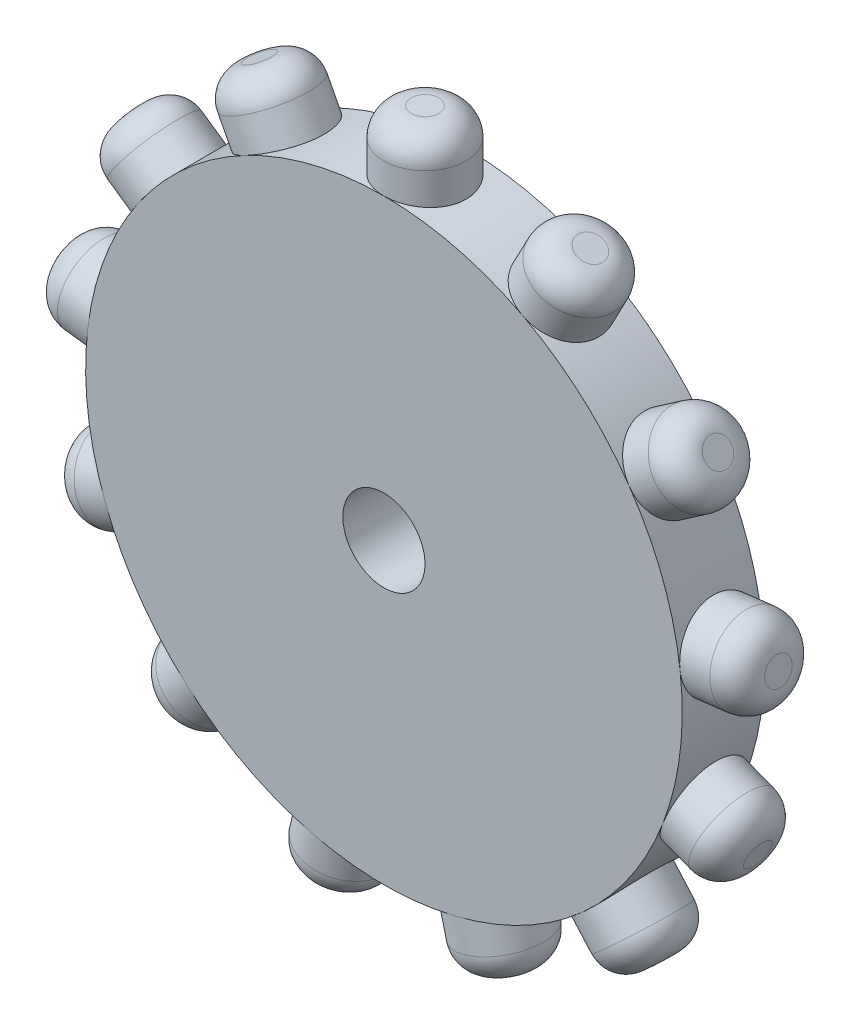
SolidWorks part; units mm, degrees
ref_plane "Front Plane" through (0, 0, 0) normal (0, 0, 1) x (1, 0, 0)
ref_plane "Top Plane" through (0, 0, 0) normal (0, 1, 0) x (1, 0, 0)
ref_plane "Right Plane" through (0, 0, 0) normal (1, 0, 0) x (0, 0, -1)
sketch "Sketch1" plane through (0, 0, 0) normal (0, 0, 1) x (1, 0, 0)
  circle A0 centre (0, 0) radius 27.6693
  dimension "D1" = 55.3385
extrude "Boss-Extrude1" add sketch "Sketch1" along normal blind 7.62
sketch "Sketch3" plane through (0, 0, 0) normal (0, 0, -1) x (-1, 0, 0)
  circle A0 centre (0, 0) radius 3.81
  dimension "D1" = 7.62
extrude "Cut-Extrude2" cut sketch "Sketch3" against normal up to next
ref_plane "Plane1" through (0, 33.02, 0) normal (0, 1, 0) x (1, 0, 0)
sketch "Sketch4" plane through (0, 33.02, 0) normal (0, 1, 0) x (1, 0, 0)
  line L0 (27.6693, 0) -> (-27.6693, 0) construction
  line L1 (-27.6693, -7.62) -> (27.6693, -7.62) construction
  line L2 (0, -55) -> (0, 55) construction
  circle A0 centre (0, -3.81) radius 3.81
extrude "Boss-Extrude3" add sketch "Sketch4" against normal up to next contours A0
fillet "Fillet3" radius 2.54 1 edges at (0, 33.02, 7.62)
pattern_circular "CirPattern3" count 13 over 360 about axis through (0, 0, 7.62) along (0, 0, -1) of "Fillet3", "Boss-Extrude3"
